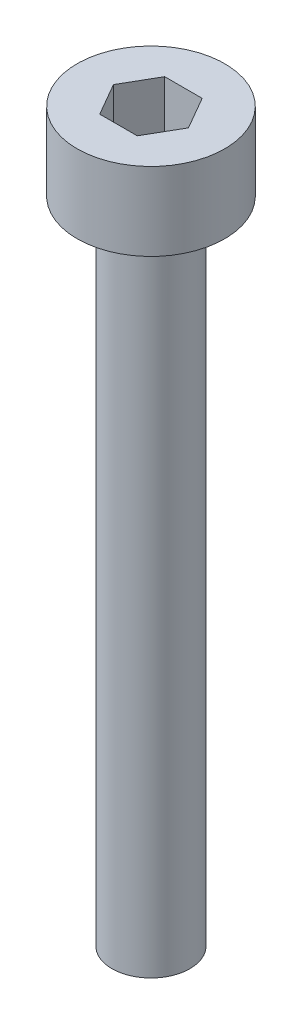
SolidWorks part; units mm, degrees
material "Plain Carbon Steel"
ref_plane "Front Plane" through (0, 0, 0) normal (0, 0, 1) x (1, 0, 0)
ref_plane "Top Plane" through (0, 0, 0) normal (0, 1, 0) x (1, 0, 0)
ref_plane "Right Plane" through (0, 0, 0) normal (1, 0, 0) x (0, 0, -1)
sketch "Sketch1" plane through (0, 0, 0) normal (0, 1, 0) x (1, 0, 0)
  line L1 (0.7217, 1.25) -> (-0.7217, 1.25)
  line L2 (-0.7217, 1.25) -> (-1.4434, 0)
  line L3 (-1.4434, 0) -> (-0.7217, -1.25)
  line L4 (-0.7217, -1.25) -> (0.7217, -1.25)
  line L5 (0.7217, -1.25) -> (1.4434, 0)
  line L6 (1.4434, 0) -> (0.7217, 1.25)
  circle A0 centre (0, 0) radius 1.25 construction
  circle A1 centre (0, 0) radius 2.84
  dimension "D1" = 5.68
  dimension "D2" = 2.5
extrude "Boss-Extrude1" add sketch "Sketch1" along normal blind 3
sketch "Sketch2" plane through (0, 0, 0) normal (0, -1, 0) x (1, 0, 0)
  circle A0 centre (0, 0) radius 1.5
  dimension "D1" = 3
extrude "Boss-Extrude2" add sketch "Sketch2" along normal blind 25
